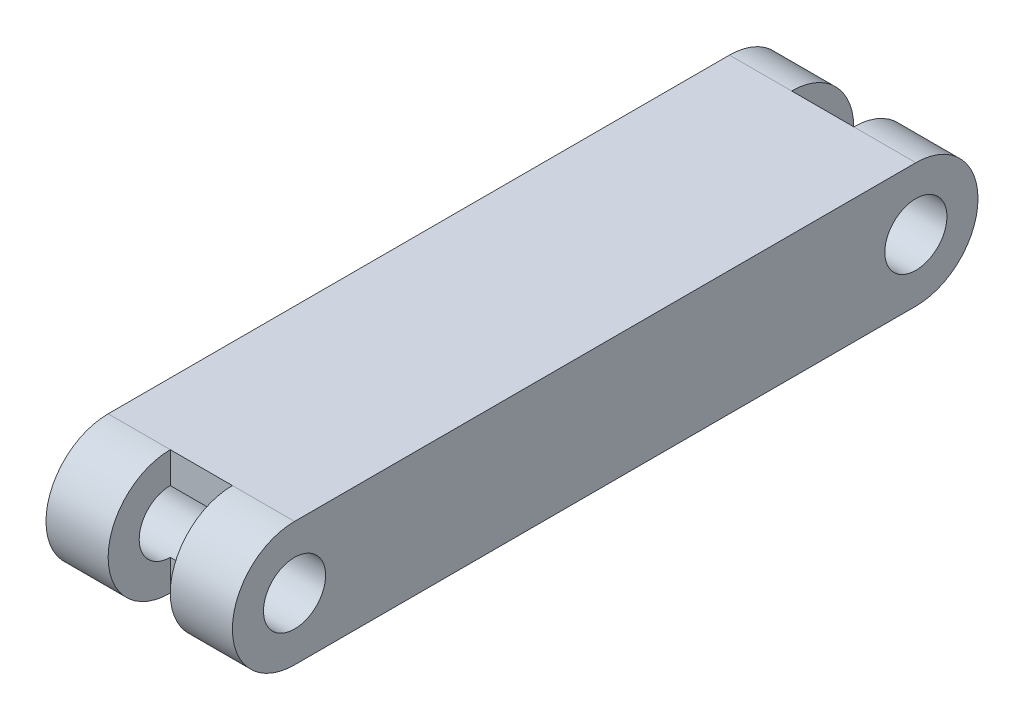
SolidWorks part; units mm, degrees
ref_plane "정면" through (0, 0, 0) normal (0, 0, 1) x (1, 0, 0)
ref_plane "윗면" through (0, 0, 0) normal (0, 1, 0) x (1, 0, 0)
ref_plane "우측면" through (0, 0, 0) normal (1, 0, 0) x (0, 0, -1)
sketch "스케치1" plane through (0, 0, 0) normal (0, 0, 1) x (1, 0, 0)
  line L1 (50, -15) -> (-10, -15)
  line L2 (50, -15) -> (50, 25)
  line L3 (50, 25) -> (-10, 25)
  line L4 (-10, -15) -> (-10, 25)
  line L5 (50, -15) -> (-10, 25) construction
  line L6 (50, 25) -> (-10, -15) construction
  dimension "D1" = 40
  dimension "D2" = 60
extrude "보스-돌출1" add sketch "스케치1" along normal blind 200
sketch "스케치6" plane through (50, 0, 0) normal (1, 0, 0) x (0, 0, -1)
  line L0 (0, -15) -> (0, 25) construction
  circle A0 centre (0, 5) radius 20
extrude "보스-돌출2" add sketch "스케치6" against normal blind 20
sketch "스케치7" plane through (-10, 0, 0) normal (-1, 0, 0) x (0, 0, 1)
  line L0 (0, 25) -> (0, -15) construction
  circle A0 centre (0, 5) radius 20
extrude "보스-돌출3" add sketch "스케치7" against normal blind 20
sketch "스케치8" plane through (-10, 0, 0) normal (-1, 0, 0) x (0, 0, 1)
  circle A0 centre (0, 5) radius 10
  dimension "D1" = 20
extrude "컷-돌출1" cut sketch "스케치8" against normal through all both and the other way through all
ref_plane "평면1" through (0, 0, 100) normal (0, 0, 1) x (1, 0, 0)
mirror "대칭 복사1" about plane through (0, 0, 100) normal (0, 0, 1) of "보스-돌출2", "컷-돌출1", "보스-돌출3"
sketch "스케치9" plane through (30, 0, 0) normal (-1, 0, 0) x (0, 0, 1)
  circle A0 centre (0, 5) radius 20
  dimension "D1" = 40
extrude "컷-돌출2" cut sketch "스케치9" along normal blind 20
